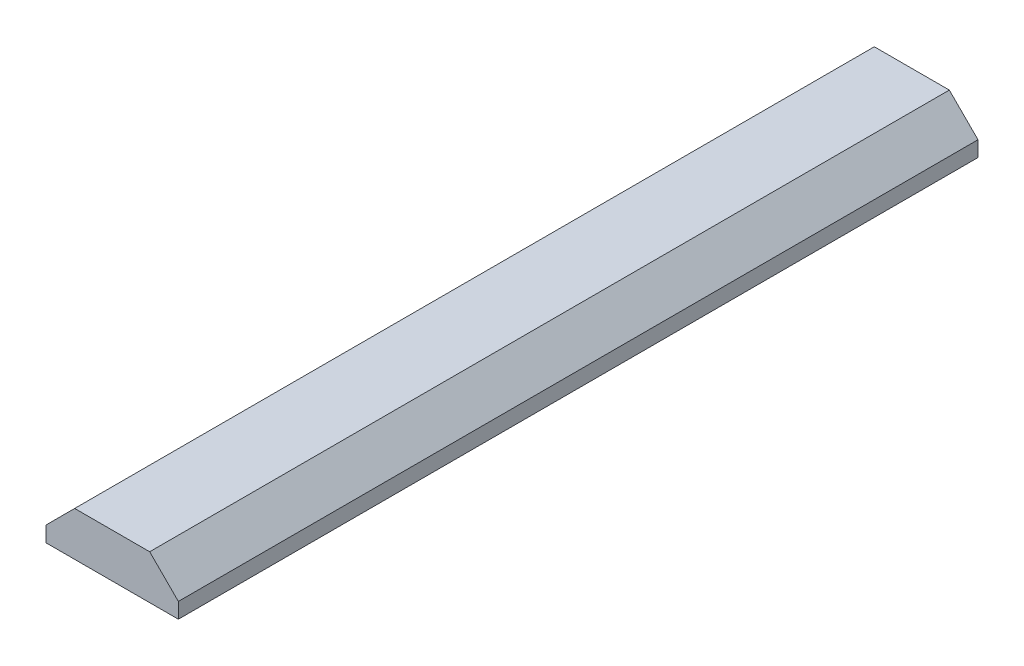
SolidWorks part; units mm, degrees
ref_plane "Ebene vorne" through (0, 0, 0) normal (0, 0, 1) x (1, 0, 0)
ref_plane "Ebene oben" through (0, 0, 0) normal (0, 1, 0) x (1, 0, 0)
ref_plane "Ebene rechts" through (0, 0, 0) normal (1, 0, 0) x (0, 0, -1)
sketch "Skizze1" plane through (0, 0, 0) normal (0, 0, 1) x (1, 0, 0)
  line L0 (0, 0) -> (0, 23680.6173) construction
  line L1 (3.4, 1.8089) -> (-3.4, 1.8089)
  line L2 (-3.4, 1.8089) -> (-6, -0.7911)
  line L3 (-6, -0.7911) -> (-6, -2.1911)
  line L4 (-6, -2.1911) -> (6, -2.1911)
  line L5 (6, -0.7911) -> (6, -2.1911)
  line L6 (3.4, 1.8089) -> (6, -0.7911)
  point P9 (0, -2.1911)
  point P11 (0, 1.8089)
  dimension "D1" = 3.4
  dimension "D2" = 6
  dimension "D3" = 4
  dimension "D4" = 135
extrude "Aufsatz-Linear austragen1" add sketch "Skizze1" along normal blind 72.5 contours L1 L2 L3 L4 L5 L6
